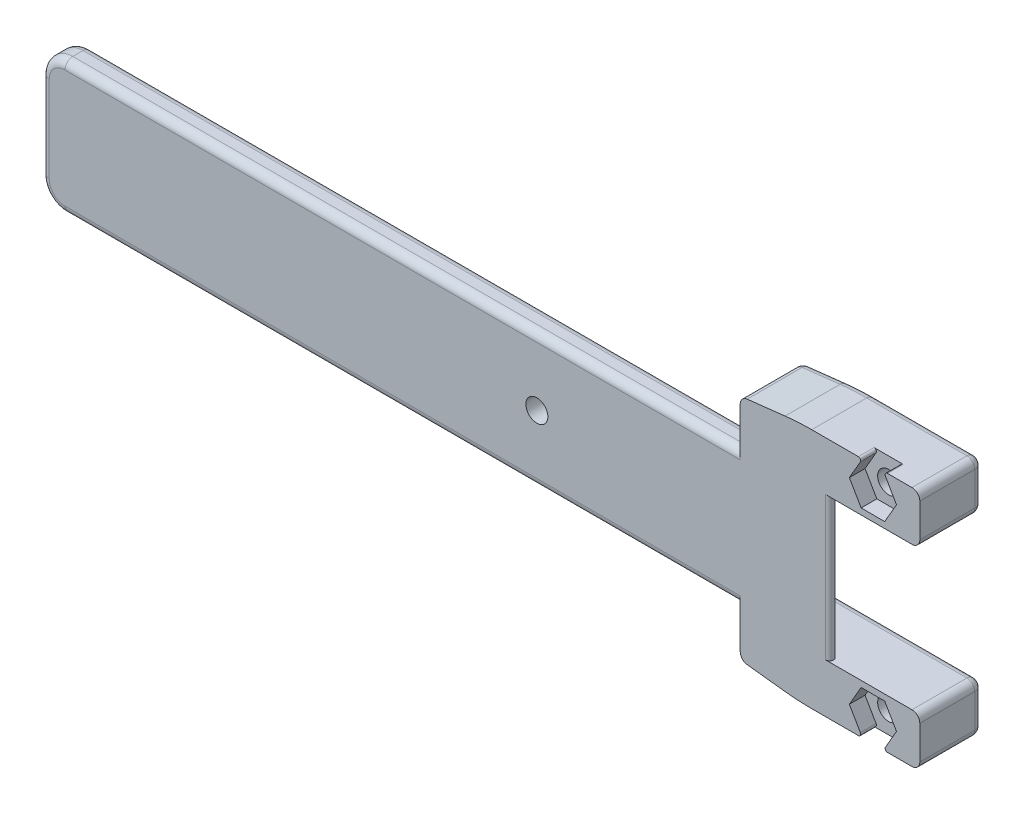
SolidWorks part; units mm, degrees
ref_plane "Front Plane" through (0, 0, 0) normal (0, 0, 1) x (1, 0, 0)
ref_plane "Top Plane" through (0, 0, 0) normal (0, 1, 0) x (1, 0, 0)
ref_plane "Right Plane" through (0, 0, 0) normal (1, 0, 0) x (0, 0, -1)
sketch "Sketch1" plane through (0, 0, 0) normal (0, 0, 1) x (1, 0, 0)
  line L0 (-2.9302, 15.4861) -> (-2.9302, 9.0208) construction
  line L1 (-2.9302, 9.0208) -> (-61.5196, 9.0208) construction
  line L2 (-18.5021, 15.4861) -> (-2.9302, 15.4861) construction
  line L3 (-2.9302, 15.4861) -> (-2.9302, 9.0208) construction
  line L4 (-2.9302, 9.0208) -> (-61.5196, 9.0208) construction
  line L5 (-18.5021, 15.4861) -> (-2.9302, 15.4861) construction
  line L6 (-61.0186, 10.642) -> (-18.5021, 15.4861) construction
  line L7 (-61.0186, 10.642) -> (-18.5021, 15.4861) construction
  line L8 (-18.5021, 15.3861) -> (-3.0302, 15.3861)
  line L9 (-3.0302, 15.3861) -> (-3.0302, 9.1208)
  line L10 (-3.0302, 9.1208) -> (-61.5196, 9.1208)
  line L11 (-18.5021, 15.3861) -> (-18.5021, 9.1208) construction
  line L12 (-61.0073, 10.5426) -> (-18.4907, 15.3868)
  line L13 (-25.9, 14.5426) -> (-25.9, 9.1208)
  line L14 (-25.9, 7.1792) -> (-25.9, -7.1792) construction
  line L15 (-25.9, 7.1792) -> (-25.9, -7.1792)
  line L16 (-18.5021, -15.4861) -> (-61.0186, -10.642) construction
  line L17 (-2.9302, -15.4861) -> (-18.5021, -15.4861) construction
  line L18 (-2.9302, -9.0208) -> (-61.5196, -9.0208) construction
  line L19 (-2.9302, -15.4861) -> (-2.9302, -9.0208) construction
  line L20 (-18.5021, -15.4861) -> (-61.0186, -10.642) construction
  line L21 (-2.9302, -15.4861) -> (-18.5021, -15.4861) construction
  line L22 (-2.9302, -9.0208) -> (-61.5196, -9.0208) construction
  line L23 (-2.9302, -15.4861) -> (-2.9302, -9.0208) construction
  line L24 (-3.0302, -9.1208) -> (-61.5196, -9.1208)
  line L25 (-3.0302, -15.3861) -> (-3.0302, -9.1208)
  line L26 (-3.0302, -15.3861) -> (-18.4964, -15.3861)
  line L27 (-18.4964, -15.3861) -> (-61.0073, -10.5426)
  line L28 (-25.9, -9.1208) -> (-25.9, -14.5426)
  circle A0 centre (-9, 12.5) radius 1.4
  circle A1 centre (-9, -12.5) radius 1.4
  dimension "D1" = 2.8
  dimension "D4" = 0.1
  dimension "D2" = 0.1
  dimension "D3" = 0.1
extrude "Boss-Extrude1" add sketch "Sketch1" along normal blind 8 contours L8 L11 L10 L9 A0 | L24 L28 L27 L26 L25 A1
sketch "Sketch2" plane through (0, 0, 8) normal (0, 0, 1) x (1, 0, 0)
  line L1 (-5.9978, 12.5) -> (-7.4989, 15.1)
  line L2 (-7.4989, 15.1) -> (-10.5011, 15.1) construction
  line L3 (-10.5011, 15.1) -> (-12.0022, 12.5)
  line L4 (-12.0022, 12.5) -> (-10.5011, 9.9)
  line L5 (-10.5011, 9.9) -> (-7.4989, 9.9)
  line L6 (-7.4989, 9.9) -> (-5.9978, 12.5)
  line L7 (-7.4989, -9.9) -> (-10.5011, -9.9)
  line L8 (-10.5011, -9.9) -> (-12.0022, -12.5)
  line L9 (-12.0022, -12.5) -> (-10.5011, -15.1)
  line L10 (-10.5011, -15.1) -> (-7.4989, -15.1) construction
  line L11 (-7.4989, -15.1) -> (-5.9978, -12.5)
  line L12 (-5.9978, -12.5) -> (-7.4989, -9.9)
  line L13 (-10.5011, 15.1) -> (-9.7189, 16.4548)
  line L14 (-9.7189, 16.4548) -> (-8.2811, 16.4548)
  line L15 (-8.2811, 16.4548) -> (-7.4989, 15.1)
  line L16 (-10.5011, -15.1) -> (-9.4683, -16.8889)
  line L17 (-9.4683, -16.8889) -> (-8.5317, -16.8889)
  line L18 (-8.5317, -16.8889) -> (-7.4989, -15.1)
  circle A0 centre (-9, 12.5) radius 2.6 construction
  circle A1 centre (-9, -12.5) radius 2.6 construction
  dimension "D1" = 5.2
extrude "Cut-Extrude1" cut sketch "Sketch2" against normal blind 2
sketch "Sketch3" plane through (0, 9.1208, 0) normal (0, -1, 0) x (1, 0, 0)
  line L0 (-61.6073, 2.5) -> (-24.2122, 2.5) construction
  line L1 (-3, 12.25) -> (-24.2122, 2.5) construction
  line L2 (-61.6073, 2.5) -> (-24.2122, 2.5) construction
  line L3 (-3, 12.25) -> (-24.2122, 2.5) construction
  line L4 (-61.6073, 2.7) -> (-24.256, 2.7)
  line L5 (-3.0835, 12.4317) -> (-24.256, 2.7)
  line L6 (-10.3359, 8) -> (-18.4964, 8) construction
  line L7 (-25.9, 8) -> (-25.9, 0) construction
  line L8 (-18.4964, 8) -> (-25.9, 8) construction
  line L9 (-10.3359, 8) -> (-18.4964, 8)
  line L10 (-25.9, 8) -> (-25.9, 0)
  line L11 (-18.4964, 8) -> (-25.9, 8)
  line M3 (-3.0302, 8) -> (-25.9, 8)
  line M4 (-25.9, 8) -> (-25.9, 0)
  dimension "D1" = 0.2
extrude "Boss-Extrude2" add sketch "Sketch3" along normal up to next contours L5 L4 M3 M4
fillet "Fillet1" radius 0.3 4 edges at (-7.6641, 15.3861, 7) (-10.3359, 15.3861, 7) (-7.6641, -15.3861, 7) (-10.3359, -15.3861, 7)
fillet "Fillet2" radius 0.5 1 edges at (-12.7252, 0, 8)
sketch "Sketch4" plane through (-25.9, 0, 0) normal (-1, 0, 0) x (0, 0, 1)
  line L0 (0, 0) -> (8, 0) construction
  line L1 (8, 14.5426) -> (8, -14.5426) construction
  line L2 (2.7, -9.1208) -> (2.7, 9.1208) construction
  line L3 (4.7, -8.5) -> (8, -8.5)
  line L4 (4.7, -8.5) -> (4.7, 8.5)
  line L5 (4.7, 8.5) -> (8, 8.5)
  line L6 (8, -8.5) -> (8, 8.5)
  line L7 (4.7, -8.5) -> (8, 8.5) construction
  line L8 (4.7, 8.5) -> (8, -8.5) construction
  point P5 (6.35, 0)
  dimension "D1" = 2
  dimension "D2" = 3.3
  dimension "D3" = 17
extrude "Boss-Extrude3" add sketch "Sketch4" along normal blind 89
fillet "Fillet3" radius 3 2 edges at (-114.9, -8.5, 6.35) (-114.9, 8.5, 6.35)
fillet "Fillet4" radius 1 8 edges at (-25.9, 9.1208, 1.35) (-25.9, -9.1208, 1.35) (-25.9, 14.5426, 4) (-25.9, -14.5426, 4) (-3.0302, -15.3861, 4) (-3.0302, 9.1208, 4) (-3.0302, 15.3861, 4) (-3.0302, -9.1208, 4)
fillet "Fillet5" radius 30 2 edges at (-18.4964, -15.3861, 4) (-18.4964, 15.3861, 4)
fillet "Fillet6" radius 1 20 edges at (-3.3231, 9.4137, 0) (-3.0302, 12.2535, 0) (-3.3231, 15.0932, 0) (-10.4115, 15.3861, 0) (-18.4936, 15.3379, 0) (-22.6011, 14.9185, 0) (-25.6461, 14.3159, 0) (-25.9, 11.8854, 0) (-25.6071, 9.4137, 0) (-3.3231, -9.4137, 0) (-3.0302, -12.2535, 0) (-3.3231, -15.0932, 0) (-10.4115, -15.3861, 0) (-18.4936, -15.3379, 0) (-22.6011, -14.9185, 0) (-25.6461, -14.3159, 0) (-25.9, -11.8854, 0) (-25.6071, -9.4137, 0) (-14.4651, 9.1208, 0) (-14.4651, -9.1208, 0)
fillet "Fillet7" radius 1 10 edges at (-68.9, -8.5, 4.7) (-114.0213, -7.6213, 4.7) (-114.9, 0, 4.7) (-114.0213, 7.6213, 4.7) (-68.9, -8.5, 8) (-114.0213, -7.6213, 8) (-114.9, 0, 8) (-114.0213, 7.6213, 8) (-68.9, 8.5, 4.7) (-68.9, 8.5, 8)
sketch "Sketch5" plane through (0, 0, 8) normal (0, 0, 1) x (1, 0, 0)
  circle A0 centre (-51.8, 0) radius 1.4
extrude "Cut-Extrude2" cut sketch "Sketch5" against normal through all
